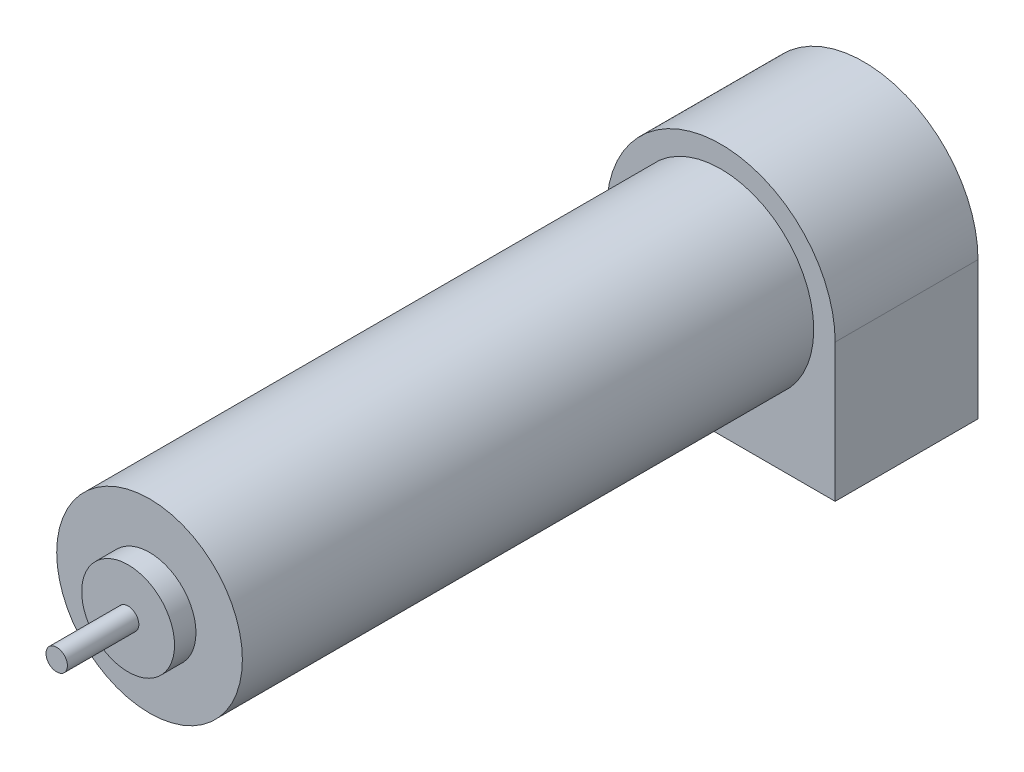
SolidWorks part; units mm, degrees
ref_plane "Plan de face" through (0, 0, 0) normal (0, 0, 1) x (1, 0, 0)
ref_plane "Plan de dessus" through (0, 0, 0) normal (0, 1, 0) x (1, 0, 0)
ref_plane "Plan de droite" through (0, 0, 0) normal (1, 0, 0) x (0, 0, -1)
sketch "Esquisse1" plane through (0, 0, 0) normal (0, 0, 1) x (1, 0, 0)
  circle A0 centre (0, 0) radius 13
  dimension "D1" = 26
extrude "Extrusion1" add sketch "Esquisse1" along normal blind 80
sketch "Esquisse2" plane through (0, 0, 80) normal (0, 0, 1) x (1, 0, 0)
  circle A0 centre (0, 0) radius 6.5
  dimension "D1" = 13
extrude "Extrusion2" add sketch "Esquisse2" along normal blind 3
sketch "Esquisse3" plane through (0, 0, 83) normal (0, 0, 1) x (1, 0, 0)
  circle A0 centre (0, 0) radius 1.5
  dimension "D1" = 3
extrude "Extrusion3" add sketch "Esquisse3" along normal blind 10
sketch "Esquisse4" plane through (0, 0, 0) normal (0, 0, -1) x (-1, 0, 0)
  line L0 (-16, 0) -> (-16, -19.3133)
  line L1 (-16, -19.3133) -> (16, -19.3133)
  line L2 (16, -19.3133) -> (16, 0)
  arc A0 (16, 0) -> (-16, 0) centre (0, 0) ccw
extrude "Extrusion5" add sketch "Esquisse4" along normal blind 20
